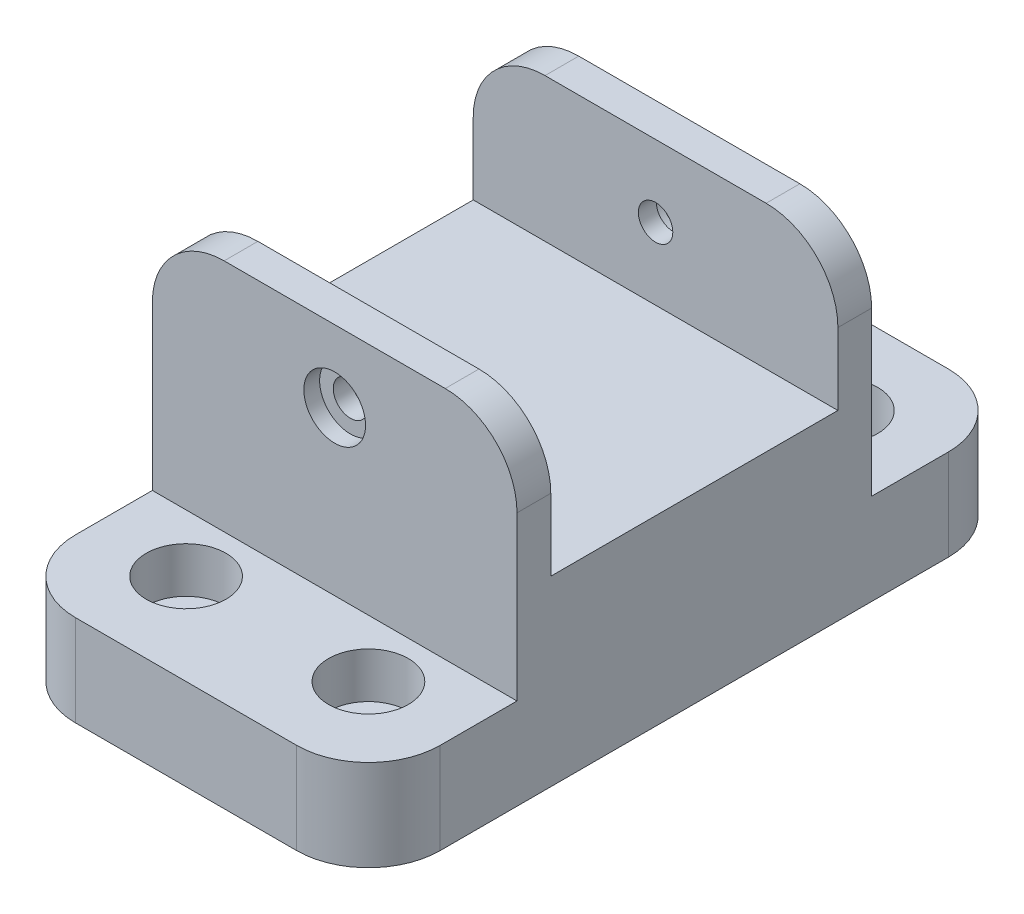
SolidWorks part; units mm, degrees
ref_plane "Front Plane" through (0, 0, 0) normal (0, 0, 1) x (1, 0, 0)
ref_plane "Top Plane" through (0, 0, 0) normal (0, 1, 0) x (1, 0, 0)
ref_plane "Right Plane" through (0, 0, 0) normal (1, 0, 0) x (0, 0, -1)
sketch "Sketch1" plane through (0, 0, 0) normal (0, 1, 0) x (1, 0, 0)
  line L1 (-23.0844, 20.5907) -> (27.7156, 20.5907)
  line L2 (-23.0844, 20.5907) -> (-23.0844, -4.8093)
  line L3 (-23.0844, -4.8093) -> (27.7156, -4.8093)
  line L4 (27.7156, 20.5907) -> (27.7156, -4.8093)
  dimension "D1" = 50.8
  dimension "D2" = 25.4
extrude "Boss-Extrude1" add sketch "Sketch1" along normal blind 25.4
sketch "Sketch2" plane through (0, 25.4, 0) normal (0, 1, 0) x (1, 0, 0)
  line L0 (27.7156, 20.5907) -> (-23.0844, 20.5907) construction
  line L1 (-10.3844, 20.5907) -> (15.0156, 20.5907)
  line L2 (-10.3844, 20.5907) -> (-10.3844, 7.8907)
  line L3 (-10.3844, 7.8907) -> (15.0156, 7.8907)
  line L4 (15.0156, 20.5907) -> (15.0156, 7.8907)
  line L5 (27.7156, -4.8093) -> (27.7156, 20.5907) construction
  line L6 (-23.0844, -4.8093) -> (27.7156, -4.8093) construction
  dimension "D1" = 12.7
  dimension "D2" = 25.4
  dimension "D3" = 12.7
hole_wizard "CBORE for 1/4 Socket Head Cap Screw1" positions "Sketch3" profile "Sketch5" counterbore size "1/4" standard "ANSI Inch" end condition through all
sketch "Sketch3" plane through (0, 25.4, 0) normal (0, 1, 0) x (1, 0, 0)
  point P0 (-10.3844, 7.8907)
  point P3 (15.0156, 7.8907)
sketch "Sketch5" plane through (-10.3844, 25.4, -7.8907) normal (1, 0, 0) x (0, 0, 1)
  line L0 (0, 0) -> (0, 25.4)
  line L1 (0, 25.4) -> (3.3782, 25.4)
  line L3 (3.3782, 25.4) -> (3.3782, 19.05)
  line L4 (3.3782, 19.05) -> (5.5562, 19.05)
  line L5 (5.5562, 19.05) -> (5.5563, 0)
  line L7 (5.5563, 0) -> (0, 0)
  line L11 (0, -6.35) -> (0, 107.95) construction
  dimension "Thru Hole Dia." = 6.7564
  dimension "Thru Hole Depth" = 25.4
  dimension "C'Bore Dia." = 11.1125
  dimension "C'Bore Depth" = 19.05
sketch "Sketch6" plane through (0, 25.4, 0) normal (0, 1, 0) x (1, 0, 0)
  line L0 (-23.0844, 20.5907) -> (-23.0844, -4.8093) construction
  line L1 (27.7156, 20.5907) -> (-23.0844, 20.5907)
  line L2 (27.7156, 20.5907) -> (27.7156, 15.8907)
  line L3 (27.7156, 15.8907) -> (-23.0844, 15.8907)
  line L4 (-23.0844, 20.5907) -> (-23.0844, 15.8907)
  circle A0 centre (15.0156, 7.8907) radius 5.5562 construction
  dimension "D1" = 8
extrude "Boss-Extrude2" add sketch "Sketch6" along normal blind 20
sketch "Sketch7" plane through (0, 0, -15.8907) normal (0, 0, 1) x (1, 0, 0)
  line L0 (-23.0844, 45.4) -> (27.7156, 45.4) construction
  line L1 (-10.3844, 45.4) -> (15.0156, 45.4)
  line L2 (-10.3844, 45.4) -> (-10.3844, 35.4)
  line L3 (-10.3844, 35.4) -> (15.0156, 35.4)
  line L4 (15.0156, 45.4) -> (15.0156, 35.4)
  line L5 (27.7156, 45.4) -> (27.7156, 25.4) construction
  line L7 (2.3156, 35.4) -> (2.3156, 45.4)
  dimension "D1" = 12.7
  dimension "D2" = 25.4
  dimension "D3" = 10
hole_wizard "CBORE for M4 SBHCS1" positions "Sketch12" profile "Sketch13" counterbore size "M4" standard "ANSI Metric" end condition through all
sketch "Sketch12" plane through (0, 0, -15.8907) normal (0, 0, 1) x (1, 0, 0)
  point P0 (2.3156, 35.4)
sketch "Sketch13" plane through (2.3156, 35.4, -15.8907) normal (1, 0, 0) x (0, -1, 0)
  line L0 (0, 0) -> (0, 4.7)
  line L1 (0, 4.7) -> (2.4, 4.7)
  line L3 (2.4, 4.7) -> (2.4, 2.2)
  line L4 (2.4, 2.2) -> (4.3, 2.2)
  line L5 (4.3, 2.2) -> (4.3, 0)
  line L7 (4.3, 0) -> (0, 0)
  line L11 (0, -6.35) -> (0, 107.95) construction
  dimension "Thru Hole Dia." = 4.8
  dimension "Thru Hole Depth" = 4.7
  dimension "C'Bore Dia." = 8.6
  dimension "C'Bore Depth" = 2.2
sketch "Sketch14" plane through (0, 0, -15.8907) normal (0, 0, 1) x (1, 0, 0)
  circle A0 centre (2.3156, 35.4) radius 5.295
fillet "Fillet1" radius 10 4 edges at (-23.0844, 45.4, -18.2407) (27.7156, 45.4, -18.2407) (27.7156, 12.7, 4.8093) (-23.0844, 12.7, 4.8093)
sketch "Sketch15" plane through (0, 0, -20.5907) normal (0, 0, -1) x (-1, 0, 0)
  line L0 (-27.7156, 35.4) -> (-27.7156, 0) construction
  line L1 (23.0844, 0) -> (-27.7156, 0)
  line L2 (23.0844, 0) -> (23.0844, 25.4)
  line L3 (23.0844, 25.4) -> (-27.7156, 25.4)
  line L4 (-27.7156, 0) -> (-27.7156, 25.4)
  dimension "D1" = 25.4
extrude "Boss-Extrude3" add sketch "Sketch15" along normal blind 20
sketch "Sketch16" plane through (0, 25.4, 0) normal (0, 1, 0) x (1, 0, 0)
  line L1 (-23.0844, 15.8907) -> (28.0289, 15.8907)
  line L2 (-23.0844, 15.8907) -> (-23.0844, -12.1026)
  line L3 (-23.0844, -12.1026) -> (28.0289, -12.1026)
  line L4 (28.0289, 15.8907) -> (28.0289, -12.1026)
extrude "Cut-Extrude2" cut sketch "Sketch16" against normal blind 12.7
mirror "Mirror1" about plane through (0, 0, -40.5907) normal (0, 0, -1) of bodies 109 107
